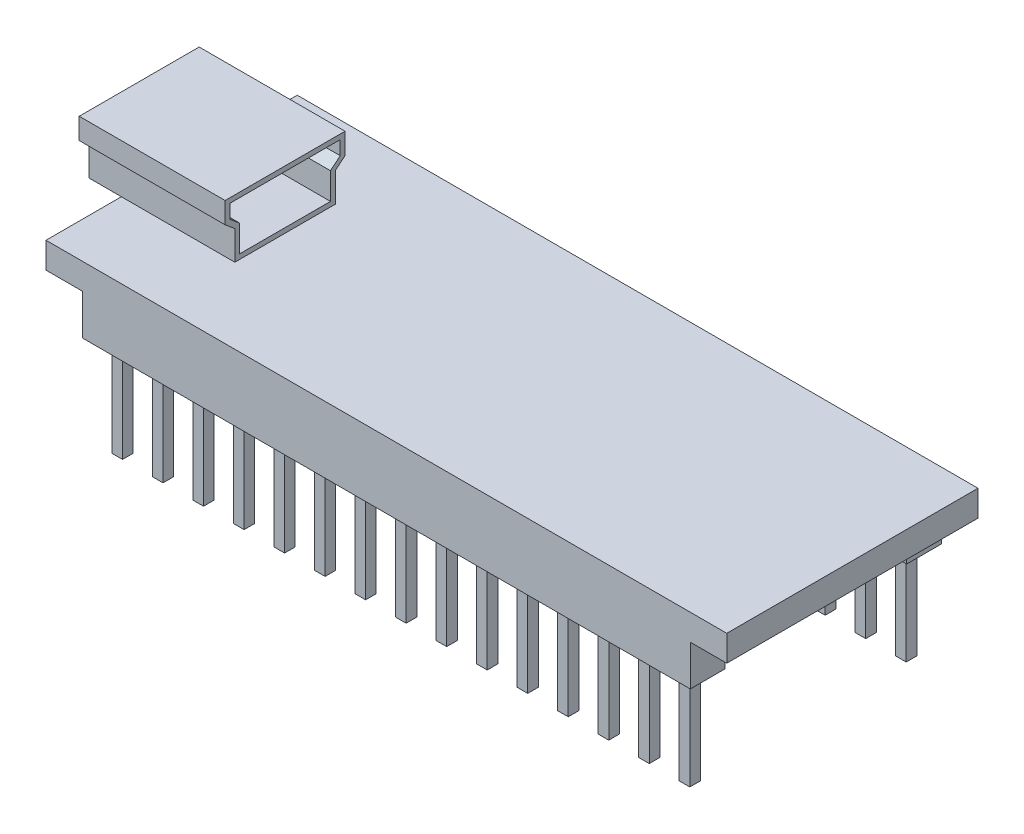
SolidWorks part; units mm, degrees
ref_plane "Front Plane" through (0, 0, 0) normal (0, 0, 1) x (1, 0, 0)
ref_plane "Top Plane" through (0, 0, 0) normal (0, 1, 0) x (1, 0, 0)
ref_plane "Right Plane" through (0, 0, 0) normal (1, 0, 0) x (0, 0, -1)
sketch "Sketch1" plane through (0, 0, 0) normal (0, 1, 0) x (1, 0, 0)
  line L1 (0, 0) -> (42, 0)
  line L2 (0, 0) -> (0, 15.5)
  line L3 (0, 15.5) -> (42, 15.5)
  line L4 (42, 0) -> (42, 15.5)
  dimension "D1" = 15.5
  dimension "D2" = 42
extrude "Boss-Extrude1" add sketch "Sketch1" along normal blind 1.6
sketch "Sketch2" plane through (0, 0, 0) normal (-1, 0, 0) x (0, 0, 1)
  line L0 (-7.75, 1.6) -> (-7.75, 5.2) construction
  line L1 (-15.5, 1.6) -> (0, 1.6) construction
  line L2 (-7.75, 1.6) -> (-10.85, 1.6)
  line L3 (-10.85, 1.6) -> (-10.85, 3.4)
  line L4 (-10.85, 3.4) -> (-11.45, 3.9)
  line L5 (-11.45, 3.9) -> (-11.45, 5.2)
  line L6 (-11.45, 5.2) -> (-7.75, 5.2)
  dimension "D1" = 3.6
  dimension "D2" = 3.7
  dimension "D3" = 3.1
  dimension "D4" = 1.8
  dimension "D5" = 1.3
extrude "Extrude-Thin1" add sketch "Sketch2" against normal blind 7 and the other way blind 2 thin
ref_plane "Plane1" through (0, 0, -7.75) normal (0, 0, 1) x (1, 0, 0)
mirror "Mirror1" about plane through (0, 0, -7.75) normal (0, 0, 1) of "Extrude-Thin1"
sketch "Sketch3" plane through (0, 0, 0) normal (0, -1, 0) x (1, 0, 0)
  line L0 (0, 0) -> (42, 0) construction
  line L1 (2.25, 0) -> (39.75, 0)
  line L2 (21, 0) -> (21, -2.1483)
  line L3 (2.25, -2.1483) -> (39.75, -2.1483)
  line L4 (39.75, 0) -> (39.75, -2.1483)
  line L5 (2.25, 0) -> (2.25, -2.1483)
  line M8 (42, 0) -> (0, 0)
  dimension "D1" = 18.75
extrude "Boss-Extrude2" add sketch "Sketch3" along normal blind 2.5 contours L1 L5 L3 L2 | L4 L2 L3 M8
sketch "Sketch4" plane through (0, -2.5, 0) normal (0, -1, 0) x (1, 0, 0)
  line L0 (2.25, -1.0741) -> (3.6453, -1.0741) construction
  line L1 (2.25, 0) -> (2.25, -2.1483) construction
  line L3 (3.9727, -0.7468) -> (3.318, -0.7468)
  line L4 (3.9727, -0.7468) -> (3.9727, -1.4015)
  line L5 (3.9727, -1.4015) -> (3.318, -1.4015)
  line L6 (3.318, -0.7468) -> (3.318, -1.4015)
  line L7 (3.9727, -0.7468) -> (3.318, -1.4015) construction
  line L8 (3.9727, -1.4015) -> (3.318, -0.7468) construction
extrude "Boss-Extrude3" add sketch "Sketch4" along normal blind 6
pattern_linear "LPattern1" count 15 spacing 2.5 along (1, 0, 0) of "Boss-Extrude3"
mirror "Mirror3" about plane through (0, 0, -7.75) normal (0, 0, 1) of "Boss-Extrude2"
mirror "Mirror4" about plane through (0, 0, -7.75) normal (0, 0, 1) of "LPattern1", "Boss-Extrude3"
